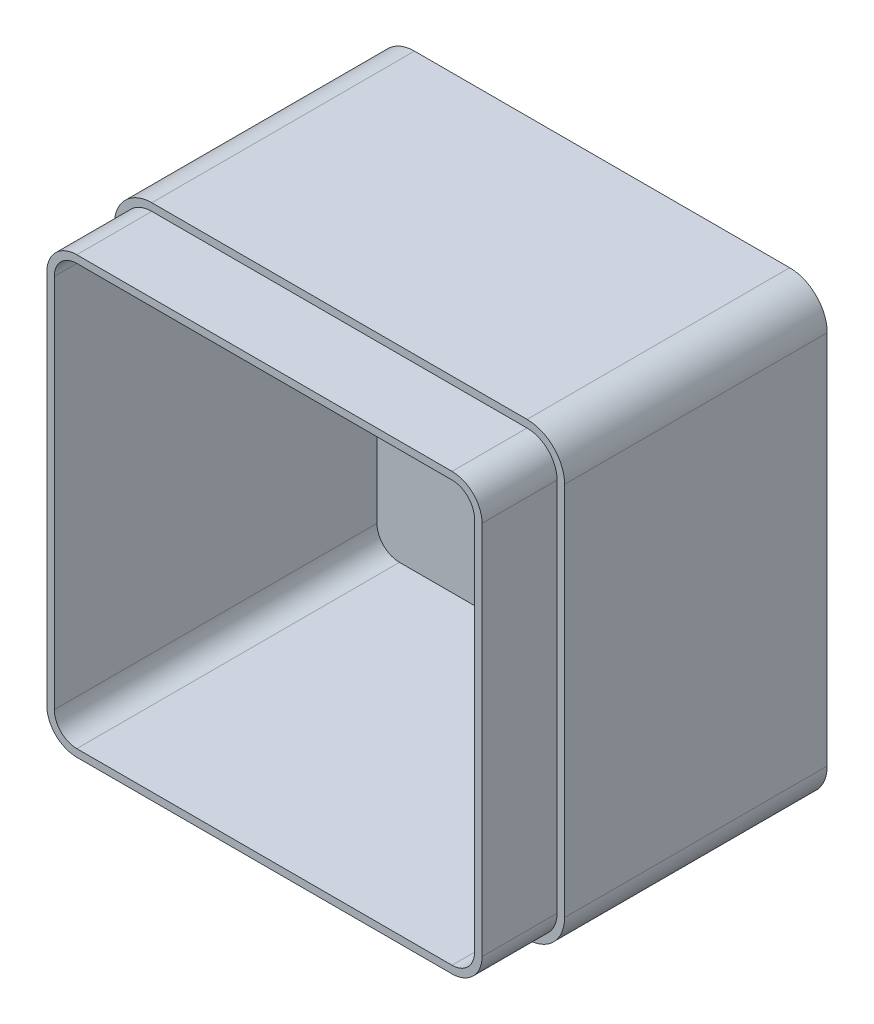
SolidWorks part; units mm, degrees
ref_plane "Front Plane" through (0, 0, 0) normal (0, 0, 1) x (1, 0, 0)
ref_plane "Top Plane" through (0, 0, 0) normal (0, 1, 0) x (1, 0, 0)
ref_plane "Right Plane" through (0, 0, 0) normal (1, 0, 0) x (0, 0, -1)
sketch "Sketch1" plane through (0, 0, 0) normal (0, 0, 1) x (1, 0, 0)
  line L1 (-60, -60) -> (60, -60)
  line L2 (-60, -60) -> (-60, 60)
  line L3 (-60, 60) -> (60, 60)
  line L4 (60, -60) -> (60, 60)
  line L5 (-60, -60) -> (60, 60) construction
  line L6 (-60, 60) -> (60, -60) construction
  point P0 (0, 0)
  dimension "D1" = 120
extrude "Boss-Extrude1" add sketch "Sketch1" along normal blind 90
fillet "Fillet1" radius 10 4 edges at (-60, 60, 45) (-60, -60, 45) (60, -60, 45) (60, 60, 45)
shell "Shell1" thickness 4
sketch "Sketch2" plane through (0, 0, 90) normal (0, 0, 1) x (1, 0, 0)
  line L0 (50, 58) -> (-50, 58)
  line L1 (-58, 50) -> (-58, -50)
  line L2 (-50, -58) -> (50, -58)
  line L3 (58, -50) -> (58, 50)
  line L4 (50, 60) -> (-50, 60)
  line L5 (-60, 50) -> (-60, -50)
  line L6 (-50, -60) -> (50, -60)
  line L7 (60, -50) -> (60, 50)
  line L8 (50, 60) -> (-50, 60)
  line L9 (-60, 50) -> (-60, -50)
  line L10 (-50, -60) -> (50, -60)
  line L11 (60, -50) -> (60, 50)
  arc A0 (-50, 58) -> (-58, 50) centre (-50, 50) ccw
  arc A1 (-58, -50) -> (-50, -58) centre (-50, -50) ccw
  arc A2 (50, -58) -> (58, -50) centre (50, -50) ccw
  arc A3 (58, 50) -> (50, 58) centre (50, 50) ccw
  arc A4 (-50, 60) -> (-60, 50) centre (-50, 50) ccw
  arc A5 (-60, -50) -> (-50, -60) centre (-50, -50) ccw
  arc A6 (50, -60) -> (60, -50) centre (50, -50) ccw
  arc A7 (60, 50) -> (50, 60) centre (50, 50) ccw
  arc A8 (-50, 60) -> (-60, 50) centre (-50, 50) ccw
  arc A9 (-60, -50) -> (-50, -60) centre (-50, -50) ccw
  arc A10 (50, -60) -> (60, -50) centre (50, -50) ccw
  arc A11 (60, 50) -> (50, 60) centre (50, 50) ccw
  line M17 (50, 60) -> (-50, 60)
  arc M18 (-50, 60) -> (-60, 50) centre (-50, 50) ccw
  line M19 (-60, 50) -> (-60, -50)
  arc M20 (-60, -50) -> (-50, -60) centre (-50, -50) ccw
  line M21 (-50, -60) -> (50, -60)
  arc M22 (50, -60) -> (60, -50) centre (50, -50) ccw
  line M23 (60, -50) -> (60, 50)
  arc M24 (60, 50) -> (50, 60) centre (50, 50) ccw
  dimension "D1" = 0
  dimension "D2" = 2
extrude "Cut-Extrude1" cut sketch "Sketch2" against normal blind 20 contours A3 L3 A2 L2 A1 L1 A0 L0 M24 M17 M18 M19 M20 M21 M22 M23
